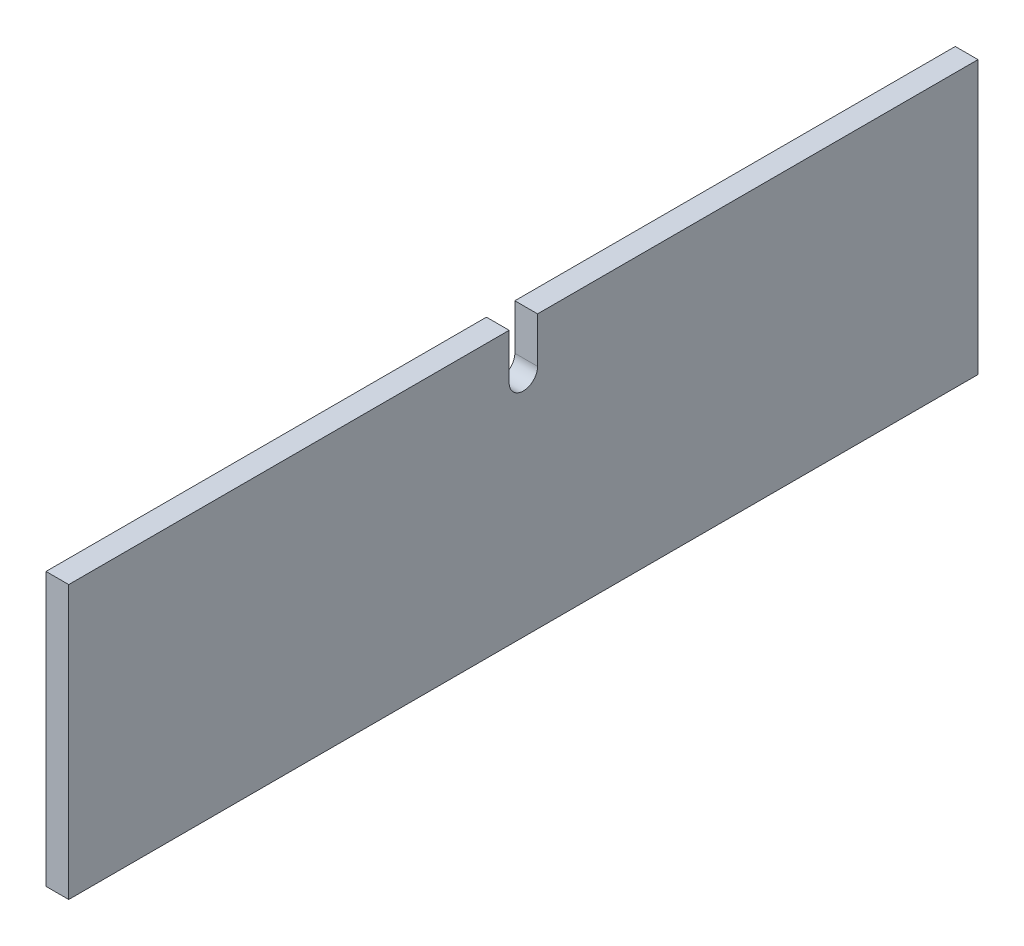
SolidWorks part; units mm, degrees
material "Custom Teakwood"
ref_plane "Front Plane" through (0, 0, 0) normal (0, 0, 1) x (1, 0, 0)
ref_plane "Top Plane" through (0, 0, 0) normal (0, 1, 0) x (1, 0, 0)
ref_plane "Right Plane" through (0, 0, 0) normal (1, 0, 0) x (0, 0, -1)
sketch "Sketch1" plane through (0, 0, 0) normal (1, 0, 0) x (0, 0, -1)
  line L0 (-15.875, 0) -> (-15.875, 50.8)
  line L1 (-508, 50.8) -> (508, 50.8)
  line L2 (-508, 50.8) -> (-508, -254)
  line L3 (-508, -254) -> (508, -254)
  line L4 (508, 50.8) -> (508, -254)
  line L5 (15.875, 0) -> (15.875, 50.8)
  arc A0 (-15.875, 0) -> (15.875, 0) centre (0, 0) ccw
  point P9 (0, 0)
  point P12 (0, 0)
  point P13 (0, 0)
  point P14 (3.0628, -6.8531)
  dimension "D4" = 508
  dimension "D1" = 254
  dimension "D2" = 50.8
  dimension "D3" = 31.75
  dimension "D5" = 508
extrude "Boss-Extrude1" add sketch "Sketch1" along normal blind 25.4 contours A0 L0 L1 L2 L3 L4 L5
